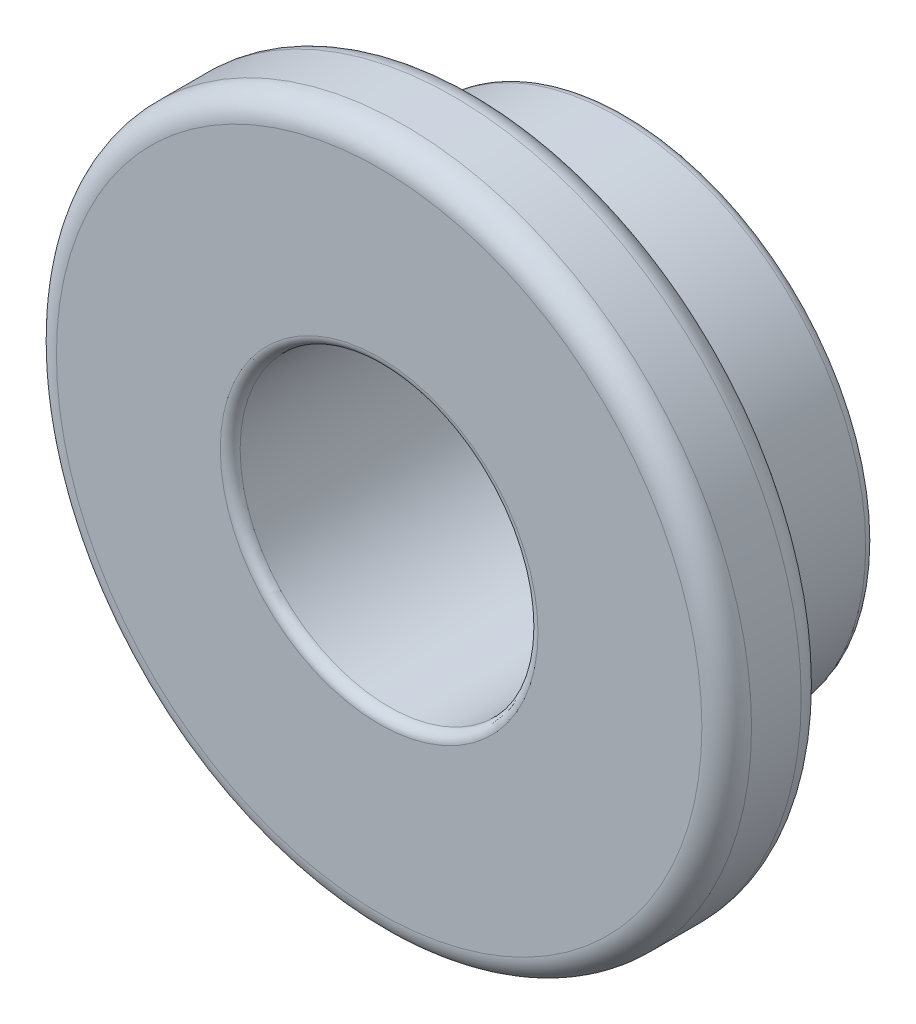
SolidWorks part; units mm, degrees
ref_plane "前视基准面" through (0, 0, 0) normal (0, 0, 1) x (1, 0, 0)
ref_plane "上视基准面" through (0, 0, 0) normal (0, 1, 0) x (1, 0, 0)
ref_plane "右视基准面" through (0, 0, 0) normal (1, 0, 0) x (0, 0, -1)
sketch "草图2" plane through (0, 0, 0) normal (0, 0, 1) x (1, 0, 0)
  circle A0 centre (0, 0) radius 7
  dimension "D1" = 14
extrude "凸台-拉伸1" add sketch "草图2" along normal blind 2
sketch "草图3" plane through (0, 0, 2) normal (0, 0, 1) x (1, 0, 0)
  circle A0 centre (0, 0) radius 5
  dimension "D1" = 10
extrude "凸台-拉伸2" add sketch "草图3" against normal blind 5
hole_wizard "Ø6.0 (6) 直径孔1" positions "草图4" profile "草图5" hole size "Ø6.0" standard "GB"
sketch "草图4" plane through (0, 0, 2) normal (0, 0, 1) x (1, 0, 0)
  point P0 (0, 0)
sketch "草图5" plane through (0, 0, 2) normal (1, 0, 0) x (0, -1, 0)
  line L0 (0, 0) -> (0, 32.1226)
  line L1 (0, 32.1226) -> (3, 30.32)
  line L2 (3, 30.32) -> (3, 0)
  line L5 (3, 0) -> (0, 0)
  line L10 (0, 32.1226) -> (-3, 30.32) construction
  line L11 (0, -6.35) -> (0, 107.95) construction
  dimension "孔直径" = 6
  dimension "孔深度" = 30.32
  dimension "导头角度" = 118
fillet "圆角1" radius 0.5 2 edges at (7, 0, 0) (7, 0, 2)
fillet "圆角2" radius 0.2 3 edges at (3, 0, 2) (3, 0, -3) (5, 0, -3)
